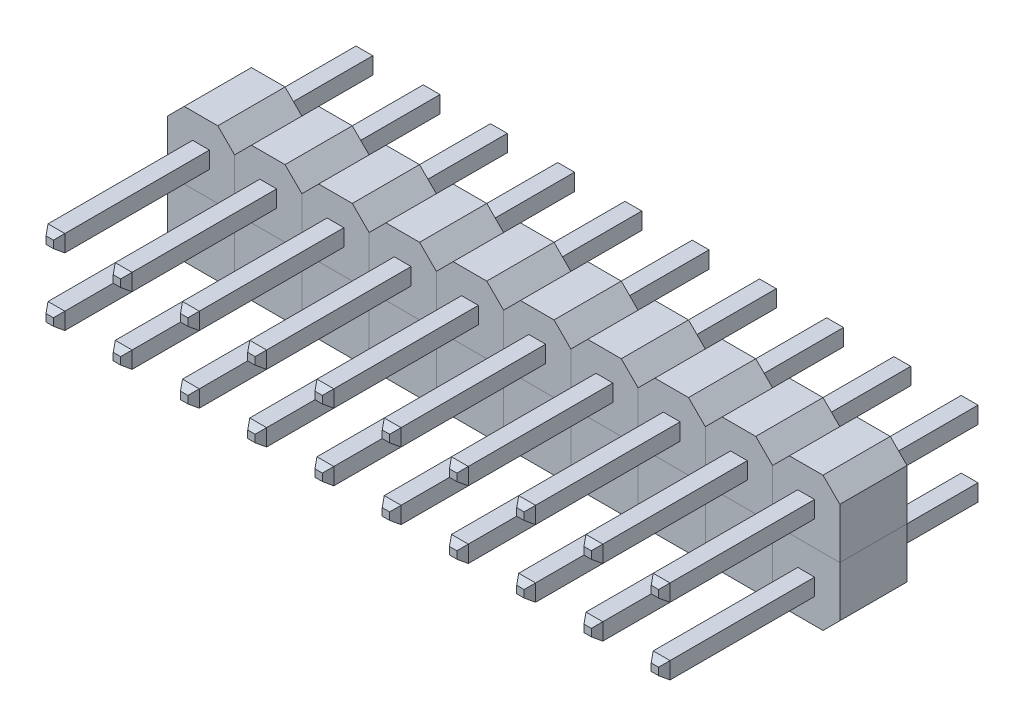
SolidWorks part; units mm, degrees
other "Детальный элемент1"
material "Ст3пс ГОСТ 14637-89"
ref_plane "Спереди" through (0, 0, 0) normal (0, 0, 1) x (1, 0, 0)
ref_plane "Сверху" through (0, 0, 0) normal (0, 1, 0) x (1, 0, 0)
ref_plane "Справа" through (0, 0, 0) normal (1, 0, 0) x (0, 0, -1)
sketch "Эскиз1" plane through (0, 0, 0) normal (0, 0, 1) x (1, 0, 0)
  line L1 (8, 2) -> (10, 2)
  line L2 (8, 2) -> (8, 0)
  line L3 (8, 0) -> (10, 0)
  line L4 (10, 2) -> (10, 0)
  line L5 (8, 2) -> (10, 0) construction
  line L6 (8, 0) -> (10, 2) construction
  point P0 (9, 1)
  dimension "D1" = 2
  dimension "D2" = 1
  dimension "D3" = 9
extrude "Бобышка-Вытянуть1" add sketch "Эскиз1" along normal blind 2
chamfer "Фаска1" distance 0.5 angle 45 2 edges at (10, 2, 1) (8, 2, 1)
pattern_linear "Линейный массив2" count 10 spacing 2 along (-1, 0, 0) of bodies 109
mirror "Зеркальное отражение1" about plane through (8, 0, 2) normal (0, 1, 0) of bodies 109 114 113 118 112 117 111 116 110 115
sketch "Эскиз2" plane through (0, 0, 2) normal (0, 0, 1) x (1, 0, 0)
  line L1 (8.75, 1.25) -> (9.25, 1.25)
  line L2 (8.75, 1.25) -> (8.75, 0.75)
  line L3 (8.75, 0.75) -> (9.25, 0.75)
  line L4 (9.25, 1.25) -> (9.25, 0.75)
  line L5 (8.75, 1.25) -> (9.25, 0.75) construction
  line L6 (8.75, 0.75) -> (9.25, 1.25) construction
  point P0 (9, 1)
  dimension "D1" = 0.5
extrude "Бобышка-Вытянуть2" add sketch "Эскиз2" along normal blind 4.5 and the other way blind 5 separate body
chamfer "Фаска2" distance 0.2 angle 35 8 edges at (8.75, 1, 6.5) (9, 1.25, 6.5) (9, 0.75, 6.5) (9.25, 1, 6.5) (9, 0.75, -3) (8.75, 1, -3) (9, 1.25, -3) (9.25, 1, -3)
pattern_linear "Линейный массив3" count 10 spacing 2 along (-1, 0, 0) count 2 spacing 2 along (0, -1, 0) of bodies 129
equation "\"N\"= 10"
equation "\"D3@Эскиз1\"=(\"N\"-1)"
equation "\"D1@Линейный массив1\"=\"N\""
